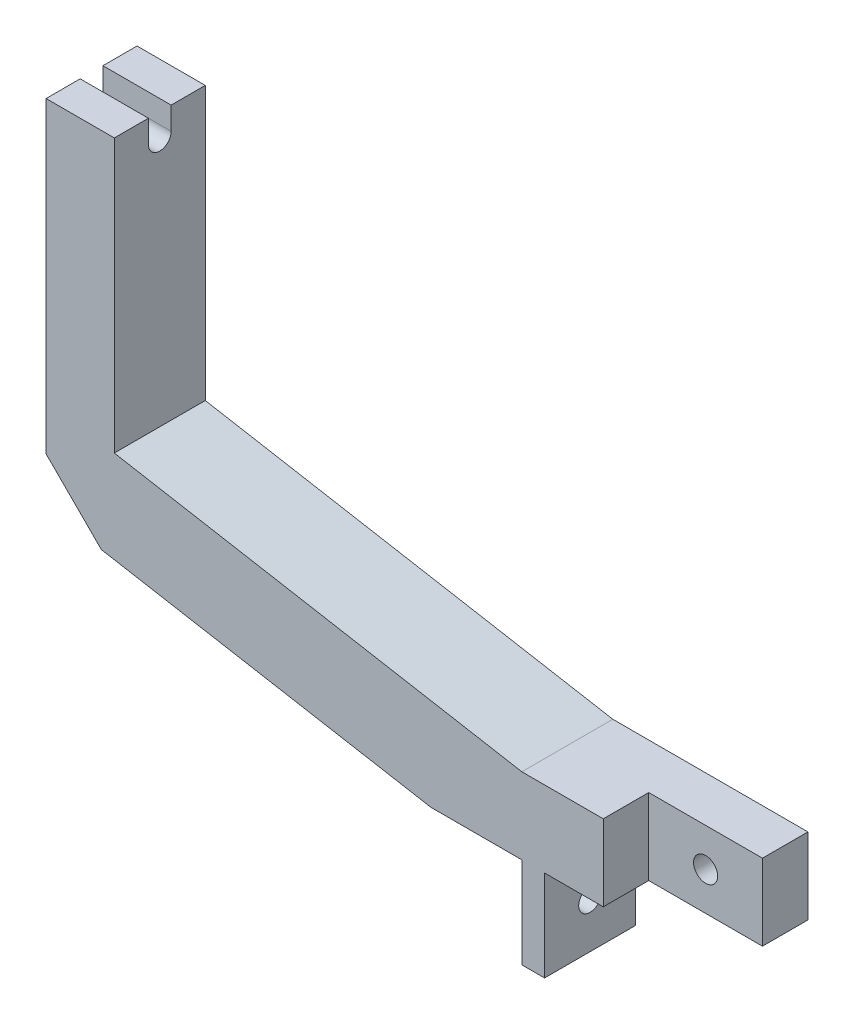
SolidWorks part; units mm, degrees
ref_plane "Front Plane" through (0, 0, 0) normal (0, 0, 1) x (1, 0, 0)
ref_plane "Top Plane" through (0, 0, 0) normal (0, 1, 0) x (1, 0, 0)
ref_plane "Right Plane" through (0, 0, 0) normal (1, 0, 0) x (0, 0, -1)
sketch "Sketch1" plane through (0, 0, 0) normal (0, 0, 1) x (1, 0, 0)
  line L0 (0, 0) -> (0, 54.9198) construction
  line L1 (32.258, 0) -> (-32.258, 0)
  line L2 (-32.258, 0) -> (-32.258, -25.4)
  line L3 (-32.258, -25.4) -> (-38.608, -25.4)
  line L4 (-38.608, -25.4) -> (-38.608, 0)
  line L5 (-38.608, 0) -> (-64.008, 0)
  line L6 (-64.008, 0) -> (-171.45, 19.05)
  line L7 (-171.45, 19.05) -> (-171.45, 117.6685)
  line L8 (-171.45, 117.6685) -> (-152.4, 117.6685)
  line L9 (-152.4, 117.6685) -> (-152.4, 41.4685)
  line L10 (-152.4, 41.4685) -> (-38.608, 21.2926)
  line L11 (-38.608, 21.2926) -> (38.608, 21.2926)
  line L12 (152.4, 41.4685) -> (38.608, 21.2926)
  line L13 (152.4, 117.6685) -> (152.4, 41.4685)
  line L14 (171.45, 117.6685) -> (152.4, 117.6685)
  line L15 (171.45, 19.05) -> (171.45, 117.6685)
  line L16 (64.008, 0) -> (171.45, 19.05)
  line L17 (38.608, 0) -> (64.008, 0)
  line L18 (38.608, -25.4) -> (38.608, 0)
  line L19 (32.258, -25.4) -> (38.608, -25.4)
  line L20 (32.258, 0) -> (32.258, -25.4)
  point P15 (0, 21.2926)
  point P24 (-85.6832, 40.0951)
  dimension "D1" = 25.4
  dimension "D2" = 19.05
  dimension "D3" = 76.2
  dimension "D4" = 19.05
  dimension "D5" = 25.4
  dimension "D6" = 304.8
  dimension "D7" = 77.216
  dimension "D8" = 6.35
  dimension "D9" = 25.4
extrude "Boss-Extrude1" add sketch "Sketch1" along normal blind 25.4
sketch "Sketch2" plane through (171.45, 0, 0) normal (1, 0, 0) x (0, 0, -1)
  line L0 (-25.4, 117.6685) -> (0, 117.6685) construction
  line L1 (-15.875, 117.6685) -> (-9.525, 117.6685)
  line L2 (-15.875, 117.6685) -> (-15.875, 111.3185)
  line L3 (-15.875, 111.3185) -> (-9.525, 111.3185) construction
  line L4 (-9.525, 117.6685) -> (-9.525, 111.3185)
  arc A0 (-9.525, 111.3185) -> (-15.875, 111.3185) centre (-12.7, 111.3185) cw
  point P7 (-12.7, 111.3185)
  point P8 (-12.7, 117.6685)
  point P9 (-12.7, 117.6685)
  dimension "D1" = 6.35
  dimension "D2" = 6.35
extrude "Cut-Extrude1" cut sketch "Sketch2" against normal through all both and the other way through all contours A0 L2 L1 L4
sketch "Sketch3" plane through (38.608, 0, 0) normal (1, 0, 0) x (0, 0, -1)
  line L0 (-25.4, -25.4) -> (0, -25.4) construction
  line L1 (-25.4, -25.4) -> (-25.4, 0) construction
  circle A0 centre (-12.7, -12.7) radius 3.175
  point P2 (-12.7, -25.4)
  point P3 (-25.4, -12.7)
  dimension "D1" = 6.35
extrude "Cut-Extrude2" cut sketch "Sketch3" against normal through all both and the other way through all
chamfer "Chamfer1" distance 12.7 angle 45 2 edges at (-171.45, 19.05, 12.7) (171.45, 19.05, 12.7)
sketch "Sketch4" plane through (0, 21.2926, 0) normal (0, 1, 0) x (1, 0, 0)
  line L0 (15.875, 0) -> (15.875, -12.7)
  line L1 (38.608, 0) -> (-38.608, 0) construction
  line L2 (15.875, -12.7) -> (-15.875, -12.7)
  line L3 (-15.875, -12.7) -> (-15.875, -25.4)
  line L4 (38.608, -25.4) -> (-38.608, -25.4) construction
  line L5 (38.608, -25.4) -> (38.608, 0) construction
  line L6 (15.875, 0) -> (187.8936, 40.7523)
  line L7 (187.8936, 40.7523) -> (246.4788, -63.9787)
  line L8 (246.4788, -63.9787) -> (141.7478, -83.6409)
  line L9 (141.7478, -83.6409) -> (-15.875, -25.4)
  point P8 (38.608, -12.7)
  point P9 (0, 0)
  point P12 (0, -12.7)
  dimension "D1" = 31.75
extrude "Cut-Extrude3" cut sketch "Sketch4" against normal through all both and the other way through all
sketch "Sketch5" plane through (0, 0, 12.7) normal (0, 0, 1) x (1, 0, 0)
  line L0 (-15.875, 21.2926) -> (15.875, 21.2926) construction
  line L1 (15.875, 0) -> (15.875, 21.2926) construction
  circle A0 centre (0, 10.6463) radius 3.3655
  point P2 (0, 21.2926)
  point P3 (15.875, 10.6463)
  dimension "D1" = 6.731
extrude "Cut-Extrude4" cut sketch "Sketch5" against normal through all both and the other way through all
